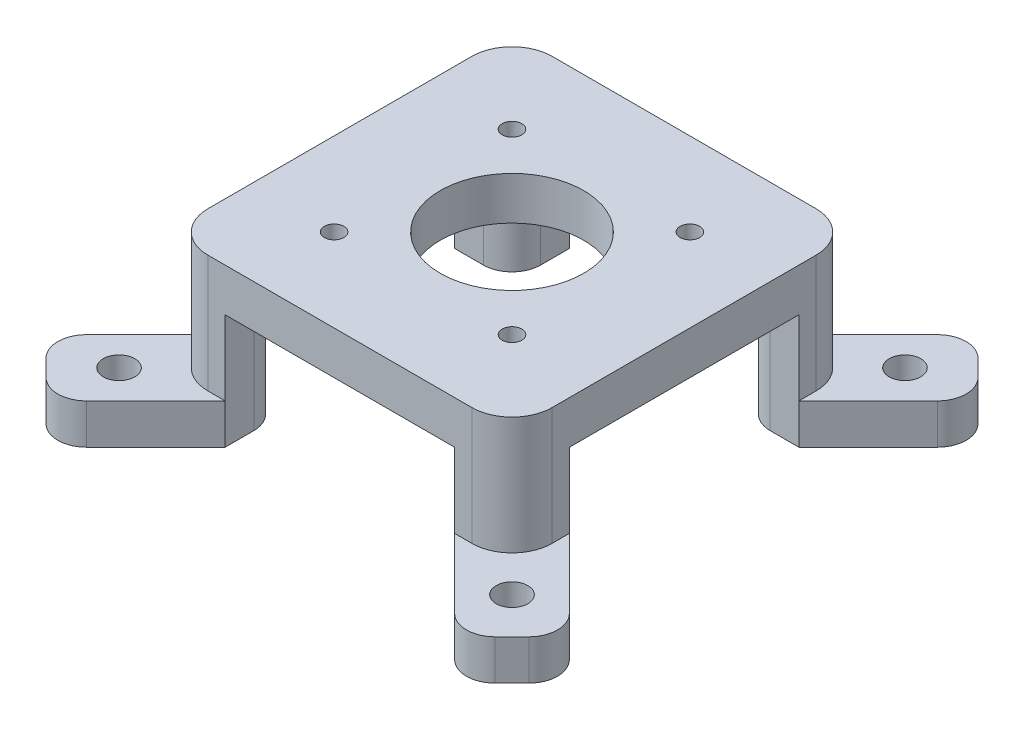
SolidWorks part; units mm, degrees
ref_plane "Front Plane" through (0, 0, 0) normal (0, 0, 1) x (1, 0, 0)
ref_plane "Top Plane" through (0, 0, 0) normal (0, 1, 0) x (1, 0, 0)
ref_plane "Right Plane" through (0, 0, 0) normal (1, 0, 0) x (0, 0, -1)
sketch "Sketch2" plane through (0, 0, 0) normal (0, 1, 0) x (1, 0, 0)
  line L0 (0, 30) -> (0, -30) construction
  line L1 (-30, 30) -> (30, 30)
  line L2 (-30, 30) -> (-30, -30)
  line L3 (-30, -30) -> (30, -30)
  line L4 (30, 30) -> (30, -30)
  line L5 (-30, 30) -> (30, -30) construction
  line L6 (-30, -30) -> (30, 30) construction
  line L7 (-30, 0) -> (30, 0) construction
  circle A0 centre (-15.5, 15.5) radius 1.7
  circle A1 centre (15.5, 15.5) radius 1.7
  circle A2 centre (-15.5, -15.5) radius 1.7
  circle A3 centre (15.5, -15.5) radius 1.7
  circle A4 centre (0, 0) radius 12.5
  point P0 (0, 0)
  dimension "D2" = 3.4
  dimension "D4" = 25
  dimension "D1" = 60
  dimension "D3" = 15.5
extrude "Boss-Extrude2" add sketch "Sketch2" along normal blind 7.5
sketch "Sketch3" plane through (0, 0, 0) normal (0, -1, 0) x (1, 0, 0)
  line L0 (0, 30) -> (0, -30) construction
  line L1 (-30, 30) -> (-20, 30)
  line L2 (-30, 30) -> (-30, 20)
  line L3 (-30, 20) -> (-20, 20)
  line L4 (-20, 30) -> (-20, 20)
  line L5 (-30, 30) -> (30, 30) construction
  line L6 (30, -30) -> (-30, -30) construction
  line L7 (-30, 0) -> (30, 0) construction
  line L8 (-30, -30) -> (-30, 30) construction
  line L9 (30, 30) -> (30, -30) construction
  line L10 (20, 30) -> (20, 20)
  line L11 (30, 20) -> (20, 20)
  line L12 (30, 30) -> (30, 20)
  line L13 (30, 30) -> (20, 30)
  line L14 (30, -30) -> (20, -30)
  line L15 (20, -30) -> (20, -20)
  line L16 (30, -30) -> (30, -20)
  line L17 (30, -20) -> (20, -20)
  line L18 (-20, -30) -> (-20, -20)
  line L19 (-30, -20) -> (-20, -20)
  line L20 (-30, -30) -> (-30, -20)
  line M5 (30, -30) -> (30, 30)
  line M6 (30, 30) -> (-30, 30)
  line M7 (-30, 30) -> (-30, -30)
  line M8 (-30, -30) -> (30, -30)
  dimension "D1" = 10
extrude "Boss-Extrude3" add sketch "Sketch3" along normal blind 20 contours L4 L3 M6 M7 | L19 L18 M7 M8 | L17 L15 M5 M8 | L11 L10 M5 M6
sketch "Sketch4" plane through (0, -20, 0) normal (0, -1, 0) x (1, 0, 0)
  line L0 (20, -30) -> (30, -30) construction
  line L1 (20, -20) -> (45, -20)
  line L2 (20, -20) -> (20, -30)
  line L3 (20, -30) -> (45, -30)
  line L4 (45, -20) -> (45, -30)
  line L5 (30, -30) -> (30, -20) construction
  line L6 (0, 30) -> (0, -30) construction
  line L7 (-20, 30) -> (20, 30) construction
  line L8 (20, -30) -> (-20, -30) construction
  line L9 (-30, 0) -> (30, 0) construction
  line L10 (-30, -20) -> (-30, 20) construction
  line L11 (30, 20) -> (30, -20) construction
  line L12 (-45, -20) -> (-45, -30)
  line L13 (-20, -30) -> (-45, -30)
  line L14 (-20, -20) -> (-20, -30)
  line L15 (-20, -20) -> (-45, -20)
  line L16 (45, 20) -> (45, 30)
  line L17 (20, 30) -> (45, 30)
  line L18 (20, 20) -> (20, 30)
  line L19 (20, 20) -> (45, 20)
  line L20 (-20, 20) -> (-45, 20)
  line L21 (-20, 20) -> (-20, 30)
  line L22 (-20, 30) -> (-45, 30)
  line L23 (-45, 20) -> (-45, 30)
  dimension "D1" = 15
extrude "Boss-Extrude4" [suppressed] add sketch "Sketch4" against normal blind 7.5
sketch "Sketch5" plane through (0, -20, 0) normal (0, -1, 0) x (1, 0, 0)
  line L0 (20, -30) -> (32.0711, -42.0711)
  line L1 (39.1421, -42.0711) -> (42.0711, -39.1421)
  line L2 (42.0711, -32.0711) -> (30, -20)
  line L3 (30, -20) -> (20, -20)
  line L4 (30, -20) -> (20, -20) construction
  line L5 (20, -30) -> (20, -20) construction
  line L6 (20, -20) -> (20, -30)
  line L7 (20, -20) -> (40.6066, -40.6066) construction
  line L8 (0, 30) -> (0, -30) construction
  line L9 (-20, 30) -> (20, 30) construction
  line L10 (20, -30) -> (-20, -30) construction
  line L11 (-30, 0) -> (30, 0) construction
  line L12 (-30, -20) -> (-30, 20) construction
  line L13 (30, 20) -> (30, -20) construction
  line L14 (-20, -20) -> (-40.6066, -40.6066) construction
  line L20 (-20, -20) -> (-20, -30)
  line L26 (-30, -20) -> (-20, -20)
  line L32 (-42.0711, -32.0711) -> (-30, -20)
  line L33 (-39.1421, -42.0711) -> (-42.0711, -39.1421)
  line L34 (-20, -30) -> (-32.0711, -42.0711)
  line L35 (20, 20) -> (40.6066, 40.6066) construction
  line L36 (20, 20) -> (20, 30)
  line L37 (30, 20) -> (20, 20)
  line L38 (42.0711, 32.0711) -> (30, 20)
  line L39 (39.1421, 42.0711) -> (42.0711, 39.1421)
  line L40 (20, 30) -> (32.0711, 42.0711)
  line L41 (-20, 20) -> (-40.6066, 40.6066) construction
  line L42 (-20, 30) -> (-32.0711, 42.0711)
  line L43 (-39.1421, 42.0711) -> (-42.0711, 39.1421)
  line L44 (-42.0711, 32.0711) -> (-30, 20)
  line L45 (-30, 20) -> (-20, 20)
  line L46 (-20, 20) -> (-20, 30)
  arc A0 (42.0711, -39.1421) -> (42.0711, -32.0711) centre (38.5355, -35.6066) ccw
  arc A1 (32.0711, -42.0711) -> (39.1421, -42.0711) centre (35.6066, -38.5355) ccw
  arc A2 (-32.0711, -42.0711) -> (-39.1421, -42.0711) centre (-35.6066, -38.5355) cw
  arc A3 (-42.0711, -39.1421) -> (-42.0711, -32.0711) centre (-38.5355, -35.6066) cw
  arc A4 (32.0711, 42.0711) -> (39.1421, 42.0711) centre (35.6066, 38.5355) cw
  arc A5 (42.0711, 39.1421) -> (42.0711, 32.0711) centre (38.5355, 35.6066) cw
  arc A6 (-42.0711, 39.1421) -> (-42.0711, 32.0711) centre (-38.5355, 35.6066) ccw
  arc A7 (-32.0711, 42.0711) -> (-39.1421, 42.0711) centre (-35.6066, 38.5355) ccw
  point P36 (-35.6066, -45.6066)
  point P37 (-45.6066, -35.6066)
  point P46 (45.6066, -35.6066)
  point P49 (35.6066, -45.6066)
  point P54 (35.6066, 45.6066)
  point P55 (45.6066, 35.6066)
  point P66 (-45.6066, 35.6066)
  point P67 (-35.6066, 45.6066)
  dimension "D2" = 5
  dimension "D1" = 15
extrude "Boss-Extrude5" add sketch "Sketch5" against normal blind 7
fillet "Fillet2" radius 7 4 edges at (30, -2.75, 30) (-30, -2.75, 30) (-30, -2.75, -30) (30, -2.75, -30)
fillet "Fillet3" radius 5 4 edges at (20, -10, 20) (-20, -10, 20) (-20, -10, -20) (20, -10, -20)
sketch "Sketch7" plane through (0, -20, 0) normal (0, -1, 0) x (1, 0, 0)
  line L0 (-40.6066, 40.6066) -> (40.6066, -40.6066) construction
  line L1 (-39.1421, 42.0711) -> (-42.0711, 39.1421) construction
  line L2 (39.1421, -42.0711) -> (42.0711, -39.1421) construction
  line L3 (40.6066, 40.6066) -> (-40.6066, -40.6066) construction
  line L4 (42.0711, 39.1421) -> (39.1421, 42.0711) construction
  line L5 (-42.0711, -39.1421) -> (-39.1421, -42.0711) construction
  circle A0 centre (34.2426, -34.2426) radius 2.75
  circle A1 centre (-34.2426, -34.2426) radius 2.75
  circle A2 centre (-34.2426, 34.2426) radius 2.75
  circle A3 centre (34.2426, 34.2426) radius 2.75
  dimension "D1" = 5.5
  dimension "D2" = 9
  dimension "D3" = 4
extrude "Cut-Extrude1" cut sketch "Sketch7" against normal through all
